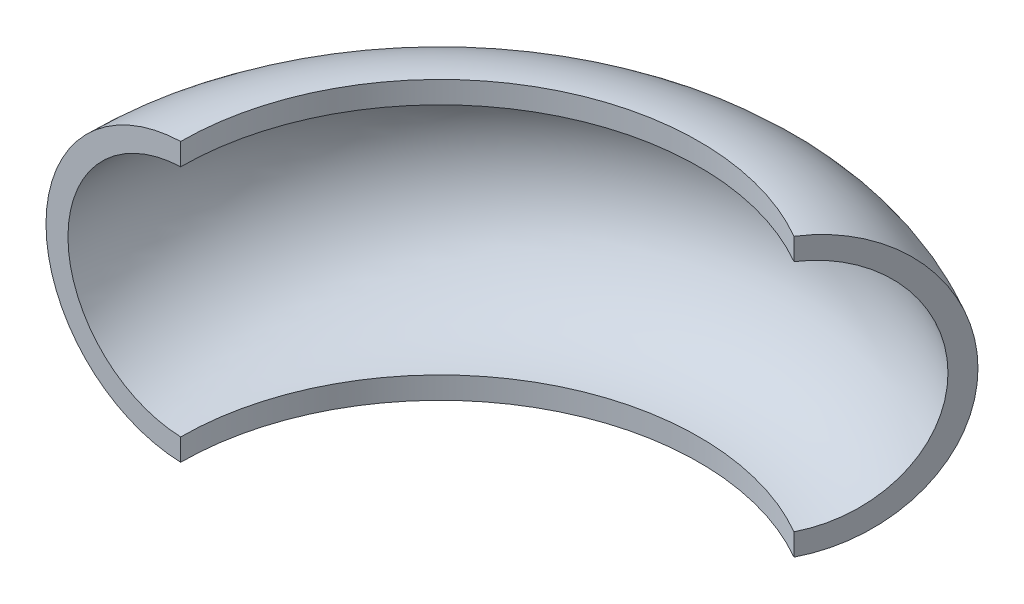
SolidWorks part; units mm, degrees
ref_plane "Front Plane" through (0, 0, 0) normal (0, 0, 1) x (1, 0, 0)
ref_plane "Top Plane" through (0, 0, 0) normal (0, 1, 0) x (1, 0, 0)
ref_plane "Right Plane" through (0, 0, 0) normal (1, 0, 0) x (0, 0, -1)
sketch "Sketch1" plane through (0, 0, 0) normal (0, 0, 1) x (1, 0, 0)
  line L2 (-0.5, 16.0972) -> (-0.5, 13.5508)
  line L3 (-0.5, -13.5508) -> (-0.5, -16.0972)
  arc A0 (-0.5, 16.0972) -> (-0.5, -16.0972) centre (0, 0) ccw
  arc A1 (-0.5, 13.5508) -> (-0.5, -13.5508) centre (0, 0) ccw
  dimension "D1" = 32.21
  dimension "D2" = 27.12
sketch "Sketch2" plane through (0, 0, 0) normal (0, 1, 0) x (1, 0, 0)
  line L0 (0, 0) -> (29.53, 0) construction
  line L1 (29.53, 0) -> (44.295, 25.5737) construction
  arc A1 (44.295, 25.5737) -> (0, 0) centre (29.53, 0) ccw
  point P3 (0, 0)
  point P4 (44.295, 25.5737)
  dimension "D1" = 29.53
  dimension "D2" = 120
sweep "Sweep1" add profiles "Sketch1" path "Sketch2"
